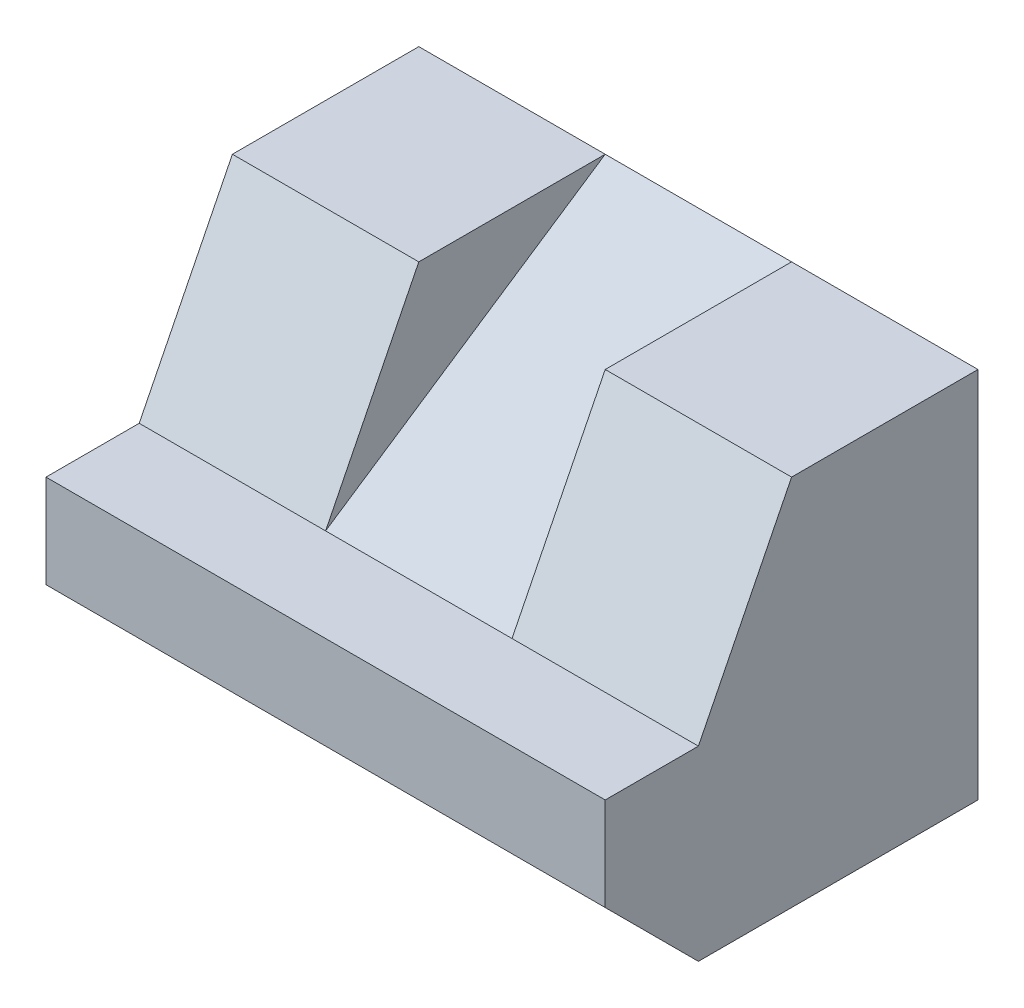
SolidWorks part; units mm, degrees
ref_plane "Front Plane" through (0, 0, 0) normal (0, 0, 1) x (1, 0, 0)
ref_plane "Top Plane" through (0, 0, 0) normal (0, 1, 0) x (1, 0, 0)
ref_plane "Right Plane" through (0, 0, 0) normal (1, 0, 0) x (0, 0, -1)
sketch "Croquis2" plane through (0, 0, 0) normal (1, 0, 0) x (0, 0, -1)
  line L0 (0, 0) -> (38.1, 0)
  line L1 (38.1, 0) -> (38.1, 50.8)
  line L2 (38.1, 50.8) -> (12.7, 50.8)
  line L3 (12.7, 50.8) -> (0, 25.4)
  line L4 (0, 25.4) -> (-12.7, 25.4)
  line L5 (-12.7, 25.4) -> (-12.7, 12.7)
  line L6 (-12.7, 12.7) -> (0, 0)
  point P3 (2.0812, 31.166)
  point P9 (-17.6602, 13.7036)
  dimension "D1" = 50.8
  dimension "D2" = 25.4
  dimension "D3" = 12.7
  dimension "D4" = 38.1
  dimension "D5" = 50.8
  dimension "D6" = 25.4
  dimension "D7" = 12.7
extrude "Saliente-Extruir2" add sketch "Croquis2" along normal blind 76.2
sketch "Croquis4" plane through (76.2, 0, 0) normal (1, 0, 0) x (0, 0, -1)
  line L0 (0, 25.4) -> (38.1, 50.8)
  line L6 (12.7, 50.8) -> (0, 25.4)
  line L7 (38.1, 50.8) -> (12.7, 50.8)
  line L8 (12.7, 50.8) -> (0, 25.4)
  line L9 (38.1, 50.8) -> (12.7, 50.8)
  dimension "D1" = 0
extrude "Cortar-Extruir3" cut sketch "Croquis4" against normal blind 25.4 from offset 25.4
